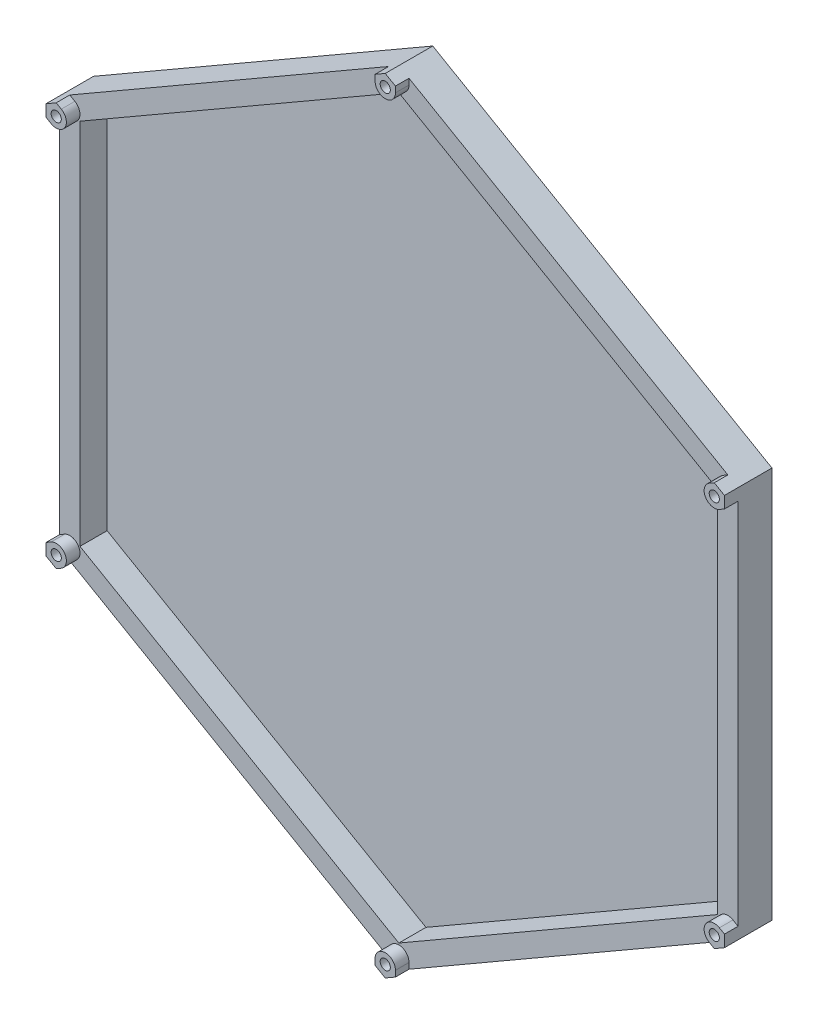
SolidWorks part; units mm, degrees
ref_plane "Front Plane" through (0, 0, 0) normal (0, 0, 1) x (1, 0, 0)
ref_plane "Top Plane" through (0, 0, 0) normal (0, 1, 0) x (1, 0, 0)
ref_plane "Right Plane" through (0, 0, 0) normal (1, 0, 0) x (0, 0, -1)
sketch "Sketch1" plane through (0, 0, 0) normal (0, 0, 1) x (1, 0, 0)
  line L0 (0, 79.5388) -> (0, -72.5077) construction
  line L1 (-90.0853, 0) -> (94.4797, 0) construction
  line L2 (0, 57.735) -> (-50, 28.8675)
  line L3 (0, 54.2709) -> (-47, 27.1355)
  line L4 (-47, 27.1355) -> (-47, -27.1355)
  line L5 (-47, -27.1355) -> (0, -54.2709)
  line L6 (0, -54.2709) -> (47, -27.1355)
  line L7 (47, -27.1355) -> (47, 27.1355)
  line L8 (47, 27.1355) -> (0, 54.2709)
  line L9 (-50, 28.8675) -> (-50, -28.8675)
  line L10 (-50, -28.8675) -> (0, -57.735)
  line L11 (0, -57.735) -> (50, -28.8675)
  line L12 (50, -28.8675) -> (50, 28.8675)
  line L13 (50, 28.8675) -> (0, 57.735)
  circle A0 centre (0, 0) radius 47 construction
  dimension "D1" = 94
  dimension "D2" = 3
extrude "Boss-Extrude1" add sketch "Sketch1" along normal blind 5
sketch "Sketch2" plane through (0, 0, 0) normal (0, 0, -1) x (-1, 0, 0)
  line L0 (-47, -27.1355) -> (-47, 27.1355) construction
  line L1 (0, -54.2709) -> (-47, -27.1355) construction
  line L2 (47, -27.1355) -> (0, -54.2709) construction
  line L3 (47, 27.1355) -> (47, -27.1355) construction
  line L4 (0, 54.2709) -> (47, 27.1355) construction
  line L5 (-47, 27.1355) -> (0, 54.2709) construction
  line L6 (-47, -27.1355) -> (-47, 27.1355)
  line L7 (0, -54.2709) -> (-47, -27.1355)
  line L8 (47, -27.1355) -> (0, -54.2709)
  line L9 (47, 27.1355) -> (47, -27.1355)
  line L10 (0, 54.2709) -> (47, 27.1355)
  line L11 (-47, 27.1355) -> (0, 54.2709)
extrude "Boss-Extrude2" add sketch "Sketch2" against normal blind 1
sketch "Sketch3" plane through (0, 0, 5) normal (0, 0, 1) x (1, 0, 0)
  line L0 (0, 57.735) -> (0, 54.2709) construction
  line L1 (0, 56.003) -> (13.3676, 56.003) construction
  line L2 (50, 28.8675) -> (0, 57.735) construction
  line L3 (0, 57.735) -> (-50, 28.8675) construction
  line L4 (50, 28.8675) -> (46.8461, 30.6884)
  line L5 (0, 57.735) -> (-1.5, 56.869)
  line L6 (-1.5, 56.003) -> (-1.5, 56.869)
  line L7 (1.5, 56.003) -> (1.5, 56.869)
  line L8 (-46.8461, 30.6884) -> (-50, 28.8675)
  line L9 (1.5, 56.869) -> (0, 57.735)
  line L10 (50, 28.8675) -> (48.5, 29.7335)
  line L11 (47.75, 29.3005) -> (48.5, 29.7335)
  line L12 (49.25, 26.7024) -> (50, 27.1355)
  line L13 (50, 27.1355) -> (50, 28.8675)
  line L14 (50, -28.8675) -> (50, -27.1355)
  line L15 (49.25, -26.7024) -> (50, -27.1355)
  line L16 (47.75, -29.3005) -> (48.5, -29.7335)
  line L17 (48.5, -29.7335) -> (50, -28.8675)
  line L18 (0, -57.735) -> (1.5, -56.869)
  line L19 (1.5, -56.003) -> (1.5, -56.869)
  line L20 (-1.5, -56.003) -> (-1.5, -56.869)
  line L21 (-1.5, -56.869) -> (0, -57.735)
  line L22 (-50, -28.8675) -> (-48.5, -29.7335)
  line L23 (-47.75, -29.3005) -> (-48.5, -29.7335)
  line L24 (-49.25, -26.7024) -> (-50, -27.1355)
  line L25 (-50, -27.1355) -> (-50, -28.8675)
  line L26 (-50, 28.8675) -> (-50, 27.1355)
  line L27 (-49.25, 26.7024) -> (-50, 27.1355)
  line L28 (-47.75, 29.3005) -> (-48.5, 29.7335)
  line L29 (-48.5, 29.7335) -> (-50, 28.8675)
  circle A0 centre (0, 0) radius 56.003 construction
  circle A1 centre (0, 56.003) radius 0.75
  arc A2 (-1.5, 56.003) -> (1.5, 56.003) centre (0, 56.003) ccw
  circle A3 centre (48.5, 28.0015) radius 0.75
  arc A4 (47.75, 29.3005) -> (49.25, 26.7024) centre (48.5, 28.0015) ccw
  circle A5 centre (48.5, -28.0015) radius 0.75
  arc A6 (49.25, -26.7024) -> (47.75, -29.3005) centre (48.5, -28.0015) ccw
  circle A7 centre (0, -56.003) radius 0.75
  arc A8 (1.5, -56.003) -> (-1.5, -56.003) centre (0, -56.003) ccw
  circle A9 centre (-48.5, -28.0015) radius 0.75
  arc A10 (-47.75, -29.3005) -> (-49.25, -26.7024) centre (-48.5, -28.0015) ccw
  circle A11 centre (-48.5, 28.0015) radius 0.75
  arc A12 (-49.25, 26.7024) -> (-47.75, 29.3005) centre (-48.5, 28.0015) ccw
  line M5 (50, 28.8675) -> (0, 57.735)
  line M6 (0, 57.735) -> (-50, 28.8675)
  line M7 (-50, 28.8675) -> (-50, -28.8675)
  line M8 (-50, -28.8675) -> (0, -57.735)
  line M9 (0, -57.735) -> (50, -28.8675)
  line M10 (50, -28.8675) -> (50, 28.8675)
  dimension "D1" = 1.5
  dimension "D2" = 6
extrude "Boss-Extrude3" add sketch "Sketch3" along normal blind 2 contours L6 A2 L7 A1 M5 M6 | L11 A4 L12 A3 M10 M5 | L15 A6 L16 A5 M9 M10 | L19 A8 L20 A7 M8 M9 | L23 A10 L24 A9 M7 M8 | L27 A12 L28 L8 A11 M7
sketch "Sketch4" plane through (0, 0, 5) normal (0, 0, 1) x (1, 0, 0)
  circle A1 centre (0, 56.003) radius 0.75
  circle A2 centre (0, 56.003) radius 0.75
  circle A3 centre (-48.5, 28.0015) radius 0.75
  circle A4 centre (-48.5, 28.0015) radius 0.75
  circle A5 centre (-48.5, -28.0015) radius 0.75
  circle A6 centre (-48.5, -28.0015) radius 0.75
  circle A7 centre (0, -56.003) radius 0.75
  circle A8 centre (0, -56.003) radius 0.75
  circle A9 centre (48.5, -28.0015) radius 0.75
  circle A10 centre (48.5, -28.0015) radius 0.75
  circle A11 centre (48.5, 28.0015) radius 0.75
  circle A12 centre (48.5, 28.0015) radius 0.75
  dimension "D1" = 0
  dimension "D2" = 0
  dimension "D3" = 0
  dimension "D4" = 0
  dimension "D5" = 0
  dimension "D6" = 0
extrude "Cut-Extrude1" cut sketch "Sketch4" against normal blind 3
